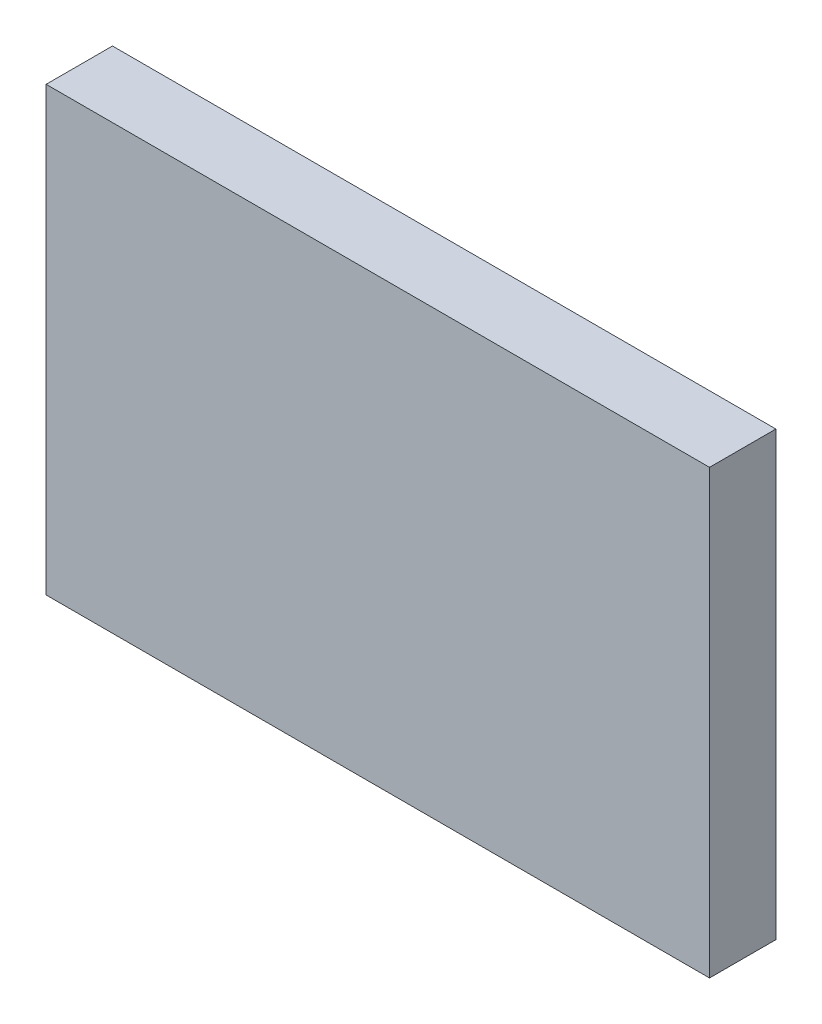
SolidWorks part; units mm, degrees
ref_plane "Alzado" through (0, 0, 0) normal (0, 0, 1) x (1, 0, 0)
ref_plane "Planta" through (0, 0, 0) normal (0, 1, 0) x (1, 0, 0)
ref_plane "Vista lateral" through (0, 0, 0) normal (1, 0, 0) x (0, 0, -1)
sketch "Croquis1" plane through (0, 0, 0) normal (0, 0, 1) x (1, 0, 0)
  line L1 (-75, -50) -> (75, -50)
  line L2 (-75, -50) -> (-75, 50)
  line L3 (-75, 50) -> (75, 50)
  line L4 (75, -50) -> (75, 50)
  line L5 (-75, -50) -> (75, 50) construction
  line L6 (-75, 50) -> (75, -50) construction
  point P0 (0, 0)
  dimension "D1" = 150
  dimension "D2" = 100
extrude "Saliente-Extruir1" add sketch "Croquis1" along normal blind 15
